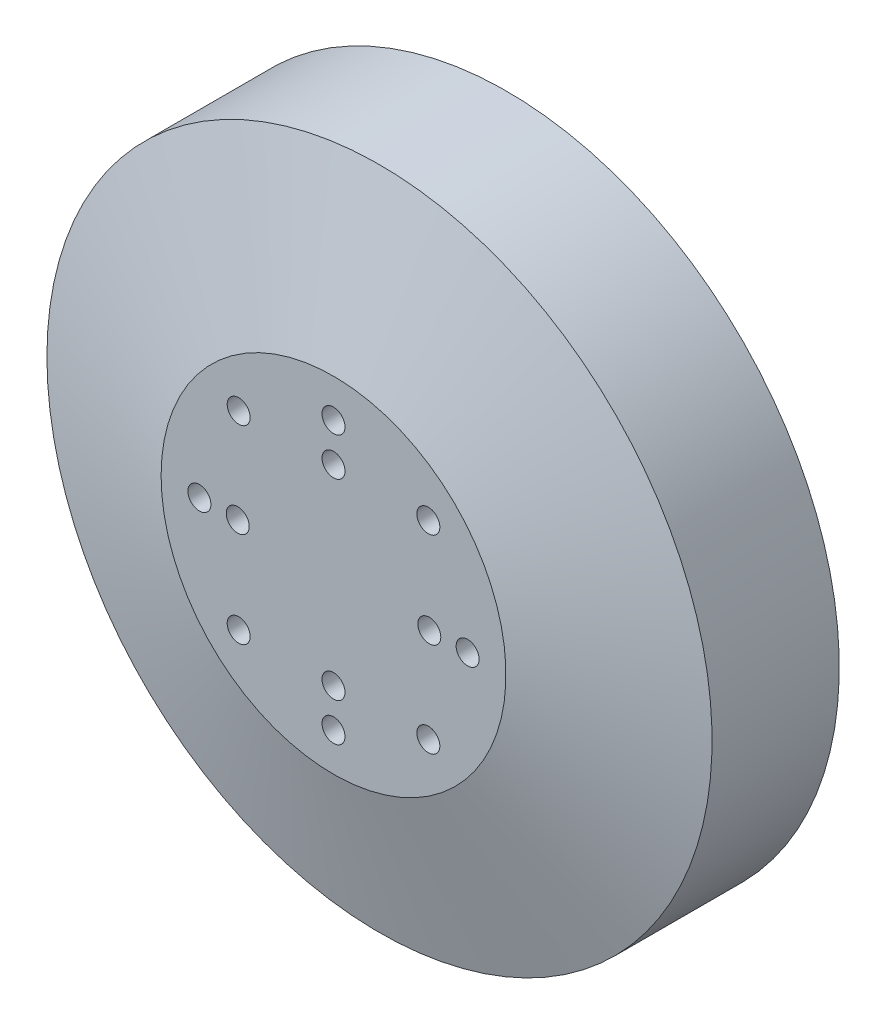
SolidWorks part; units mm, degrees
ref_plane "Front Plane" through (0, 0, 0) normal (0, 0, 1) x (1, 0, 0)
ref_plane "Top Plane" through (0, 0, 0) normal (0, 1, 0) x (1, 0, 0)
ref_plane "Right Plane" through (0, 0, 0) normal (1, 0, 0) x (0, 0, -1)
sketch "Sketch1" plane through (0, 0, 0) normal (0, 0, 1) x (1, 0, 0)
  circle A0 centre (0, 0) radius 43.4
  dimension "D1" = 86.8
extrude "Boss-Extrude1" add sketch "Sketch1" along normal mid plane 26.6
sketch "Sketch2" plane through (0, 0, 0) normal (0, 1, 0) x (1, 0, 0)
  line L0 (-22.5, -13.3) -> (22.5, -13.3) construction
  line L1 (-43.4, -13.3) -> (43.4, -13.3) construction
  line L2 (-43.4, -7.3) -> (-22.5, -13.3)
  line L3 (-43.4, 13.3) -> (-43.4, -13.3) construction
  line L4 (-43.4, 9.3) -> (-43.4, 13.3)
  line L6 (-20, 13.3) -> (20, 13.3) construction
  line L7 (43.4, 13.3) -> (-43.4, 13.3) construction
  line L8 (-20, 13.3) -> (-40.4, 10.8)
  line L9 (-40.4, 10.8) -> (-40.4, 9.3)
  line L10 (-40.4, 9.3) -> (-43.4, 9.3)
  line L11 (-43.4, -13.3) -> (43.4, -13.3) construction
  line L12 (43.4, 13.3) -> (-43.4, 13.3) construction
  line L13 (-43.4, 13.3) -> (-43.4, -13.3) construction
  line L14 (0, 13.3) -> (0, -13.3) construction
  line L15 (-43.4, 13.3) -> (-20, 13.3)
  line L16 (-43.4, -7.3) -> (-43.4, -13.3)
  line L17 (-43.4, -13.3) -> (-22.5, -13.3)
  point P5 (0, -13.3)
  point P17 (0, 13.3)
  dimension "D1" = 45
  dimension "D2" = 40
  dimension "D3" = 6
  dimension "D4" = 4
  dimension "D5" = 1.5
  dimension "D6" = 3
revolve "Cut-Revolve1" cut sketch "Sketch2" angle 360 about L14
sketch "Sketch3" plane through (0, 0, -13.3) normal (0, 0, -1) x (-1, 0, 0)
  line L1 (10.6066, -10.6066) -> (-10.6066, -10.6066) construction
  line L2 (10.6066, -10.6066) -> (10.6066, 10.6066) construction
  line L3 (10.6066, 10.6066) -> (-10.6066, 10.6066) construction
  line L4 (-10.6066, -10.6066) -> (-10.6066, 10.6066) construction
  line L5 (10.6066, -10.6066) -> (-10.6066, 10.6066) construction
  line L6 (10.6066, 10.6066) -> (-10.6066, -10.6066) construction
  circle A0 centre (0, 0) radius 16 construction
  circle A1 centre (0, 0) radius 15 construction
  circle A3 centre (10.6066, 10.6066) radius 1.5
  circle A5 centre (10.6066, -10.6066) radius 1.5
  circle A7 centre (-10.6066, -10.6066) radius 1.5
  circle A9 centre (-10.6066, 10.6066) radius 1.5
  circle A10 centre (0, 16) radius 2
  circle A11 centre (16, 0) radius 2
  circle A12 centre (0, -16) radius 2
  circle A13 centre (-16, 0) radius 2
  point P4 (-8.8001, 8.8001)
  point P5 (-8.8001, -9.33)
  point P6 (8.8001, -8.3415)
  point P13 (10.6401, 10.573)
  point P15 (0, 0)
  point P16 (-10.6066, 10.6066)
  point P23 (0, 0)
  point P32 (0, 0)
  dimension "D1" = 32
  dimension "D2" = 30
  dimension "D3" = 3
  dimension "D5" = 4
  dimension "D6" = 4
extrude "Cut-Extrude1" cut sketch "Sketch3" against normal blind 10
sketch "Sketch4" plane through (0, 0, 13.3) normal (0, 0, 1) x (1, 0, 0)
  circle A0 centre (0, 0) radius 17.5 construction
  circle A1 centre (0, 0) radius 12.5 construction
  circle A2 centre (0, 17.5) radius 1.5
  circle A3 centre (0, 12.5) radius 1.5
  circle A4 centre (12.3744, 12.3744) radius 1.5
  circle A5 centre (17.5, 0) radius 1.5
  circle A6 centre (12.3744, -12.3744) radius 1.5
  circle A7 centre (0, -17.5) radius 1.5
  circle A8 centre (-12.3744, -12.3744) radius 1.5
  circle A9 centre (-17.5, 0) radius 1.5
  circle A10 centre (-12.3744, 12.3744) radius 1.5
  circle A11 centre (12.5, 0) radius 1.5
  circle A12 centre (0, -12.5) radius 1.5
  circle A13 centre (-12.5, 0) radius 1.5
  point P8 (0, -12.5)
  point P9 (0, -17.5)
  point P25 (0, 0)
  point P32 (0, 0)
  dimension "D1" = 35
  dimension "D2" = 25
  dimension "D3" = 3
  dimension "D4" = 8
  dimension "D5" = 4
extrude "Cut-Extrude2" cut sketch "Sketch4" against normal blind 5
